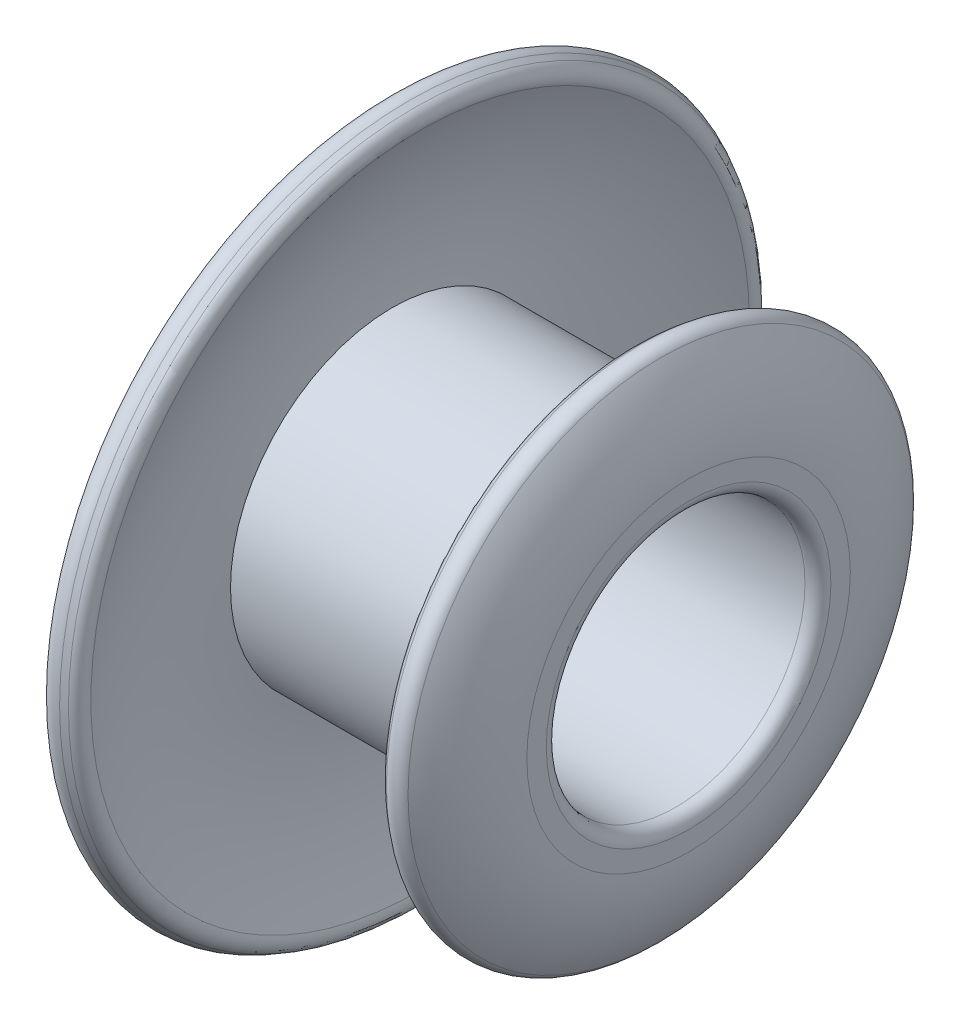
SolidWorks part; units mm, degrees
ref_plane "XY PLANE" through (0, 0, 0) normal (0, 0, 1) x (1, 0, 0)
ref_plane "ZX PLANE" through (0, 0, 0) normal (0, 1, 0) x (1, 0, 0)
ref_plane "YZ PLANE" through (0, 0, 0) normal (1, 0, 0) x (0, 0, -1)
sketch "Sketch1" plane through (0, 0, 0) normal (0, 0, 1) x (1, 0, 0)
  line L0 (0, 0) -> (-2.2212, 0) construction
  line L1 (0, 1.25) -> (-2, 1.25)
  line L2 (-2.25, 1) -> (0.25, 1)
  line L3 (-1.781, 2.6294) -> (-2, 2.75)
  line L4 (-2, 1.25) -> (-2.0406, 1.25)
  line L5 (0.25, 1) -> (0.25, 1.25)
  line L6 (-0.031, 2.0396) -> (-0.2248, 1.8817)
  arc A0 (-2.25, 1) -> (-2, 2.75) centre (0.19, 1.5443) cw
  arc A1 (-2.0406, 1.25) -> (-1.781, 2.6294) centre (0.19, 1.5443) cw
  arc A2 (-2.006, 1.0544) -> (-1.781, 2.6294) centre (0.19, 1.5443) cw construction
  arc A3 (0.25, 1.25) -> (-0.031, 2.0396) centre (-1, 1.25) ccw
  arc A4 (0, 1.25) -> (-0.2248, 1.8817) centre (-1, 1.25) ccw
  dimension "D6" = 2.5
  dimension "D9" = 1.25
  dimension "D1" = 1.25
  dimension "D2" = 2
  dimension "D3" = 0.25
  dimension "D4" = 0.25
  dimension "D5" = 0.25
  dimension "D7" = 1.5
  dimension "D10" = 1.75
  dimension "D8" = 0.25
  dimension "D11" = 0.25
revolve "Revolve1" add sketch "Sketch1" angle 360 about L0
fillet "Fillet1" radius 0.1 6 edges at (-2.25, 0, -1) (0.25, 0, -1) (-0.031, 0, -2.0396) (-0.2248, 0, -1.8817) (-1.781, 0, -2.6294) (-2, 0, -2.75)
